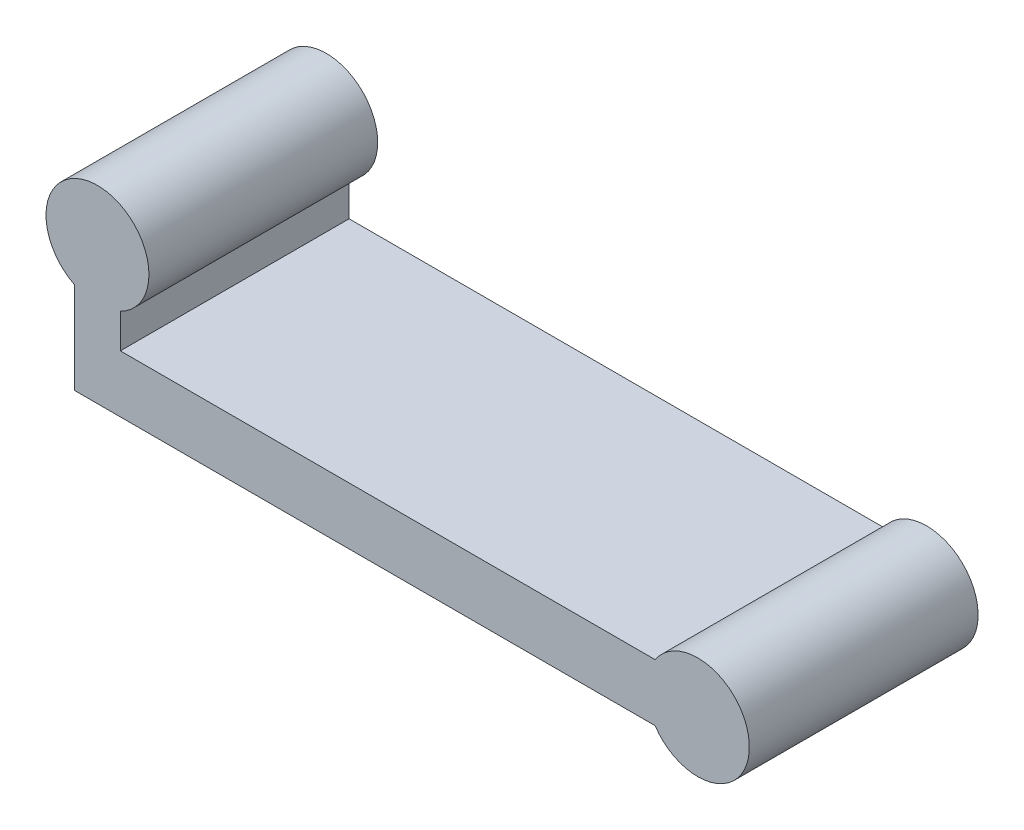
SolidWorks part; units mm, degrees
ref_plane "Front Plane" through (0, 0, 0) normal (0, 0, 1) x (1, 0, 0)
ref_plane "Top Plane" through (0, 0, 0) normal (0, 1, 0) x (1, 0, 0)
ref_plane "Right Plane" through (0, 0, 0) normal (1, 0, 0) x (0, 0, -1)
sketch "Sketch1" plane through (0, 0, 0) normal (0, 0, 1) x (1, 0, 0)
  line L0 (0, 1.6) -> (0, 0)
  line L1 (0, 0) -> (10.15, 0)
  line L2 (10.15, 0) -> (10.15, 1) construction
  line L3 (10.15, 1) -> (0.8, 1)
  line L4 (0.8, 1) -> (0.8, 1.6)
  line L5 (0.8, 1.6) -> (0, 1.6) construction
  arc A0 (0, 1.6) -> (0.8, 1.6) centre (0.4, 2.4062) cw
  arc A1 (10.15, 1) -> (10.15, 0) centre (10.8983, 0.5) cw
  point P9 (0.4, 1.6)
  dimension "D3" = 0.9
  dimension "D4" = 0.9
  dimension "D1" = 0.8
  dimension "D2" = 1
  dimension "D5" = 9.75
  dimension "D6" = 0.6
  dimension "D7" = 10.4983
extrude "Boss-Extrude1" add sketch "Sketch1" along normal blind 4
